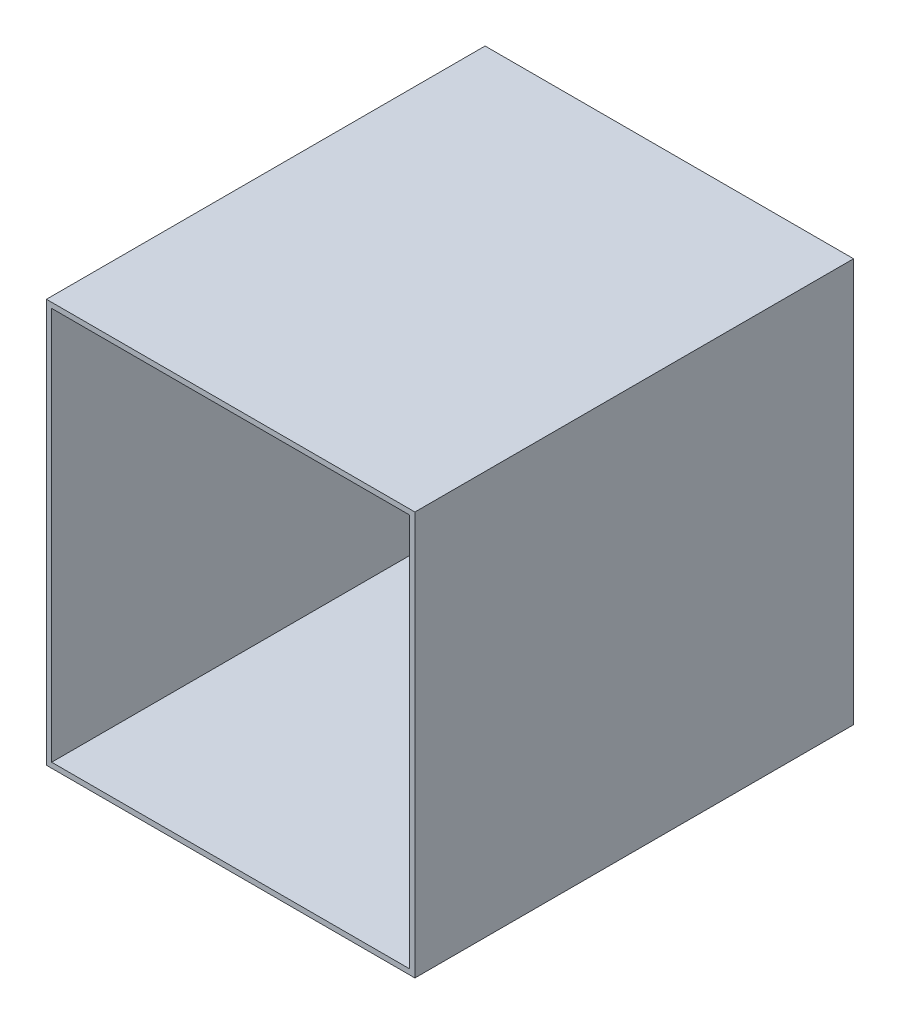
SolidWorks part; units mm, degrees
ref_plane "Front Plane" through (0, 0, 0) normal (0, 0, 1) x (1, 0, 0)
ref_plane "Top Plane" through (0, 0, 0) normal (0, 1, 0) x (1, 0, 0)
ref_plane "Right Plane" through (0, 0, 0) normal (1, 0, 0) x (0, 0, -1)
sketch "Sketch1" plane through (0, 0, 0) normal (0, 0, 1) x (1, 0, 0)
  line L0 (-164.2502, 0) -> (45.7498, 0)
  line L1 (-164.2502, 0) -> (-164.2502, 230)
  line L2 (-164.2502, 230) -> (45.7498, 230)
  line L3 (45.7498, 230) -> (45.7498, 0)
  line L4 (42.7498, 3) -> (-161.2502, 3)
  line L5 (-161.2502, 3) -> (-161.2502, 227)
  line L6 (-161.2502, 227) -> (42.7498, 227)
  line L7 (42.7498, 227) -> (42.7498, 3)
  dimension "D1" = 3
  dimension "D2" = 3
  dimension "D3" = 3
  dimension "D4" = 3
  dimension "D5" = 230
  dimension "D6" = 210
extrude "Boss-Extrude1" add sketch "Sketch1" along normal blind 250
